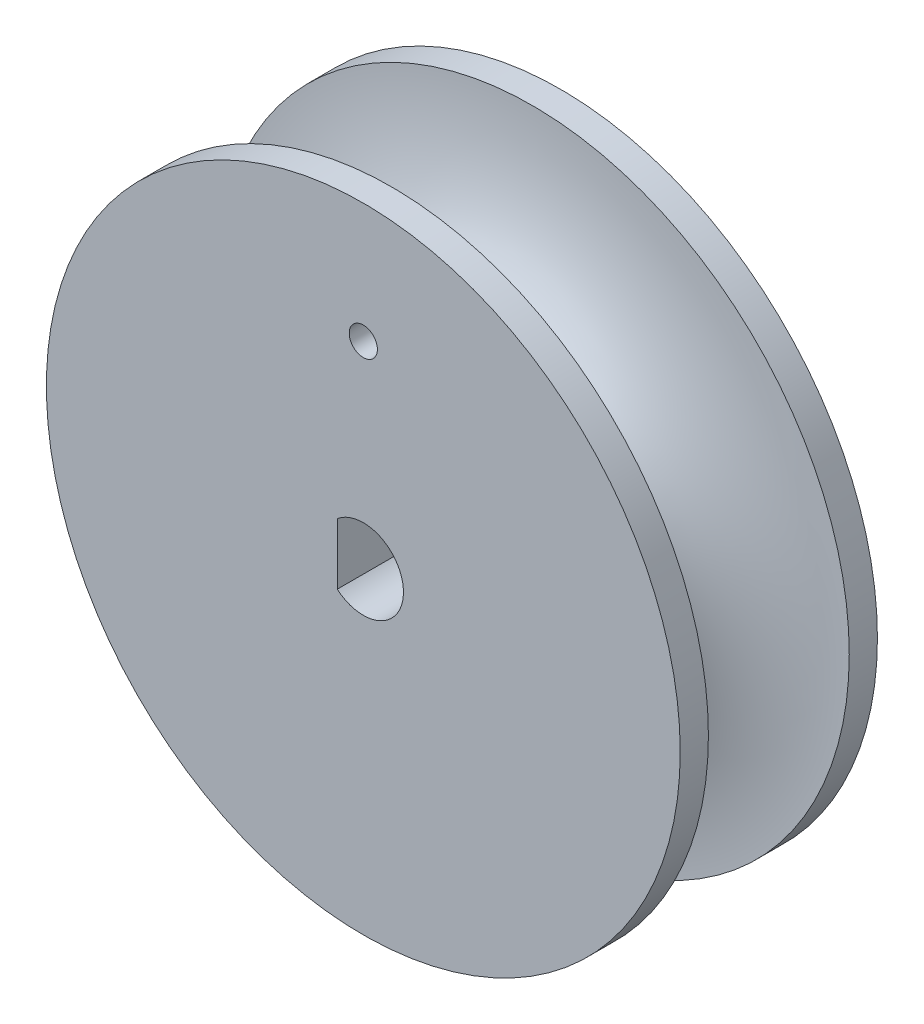
SolidWorks part; units mm, degrees
ref_plane "Front Plane" through (0, 0, 0) normal (0, 0, 1) x (1, 0, 0)
ref_plane "Top Plane" through (0, 0, 0) normal (0, 1, 0) x (1, 0, 0)
ref_plane "Right Plane" through (0, 0, 0) normal (1, 0, 0) x (0, 0, -1)
sketch "Sketch4" plane through (0, 0, 0) normal (1, 0, 0) x (0, 0, -1)
  line L0 (0, 0) -> (10.7579, 0) construction
  line L1 (-3.5, 11.25) -> (3.5, 11.25)
  line L2 (-3.5, 11.25) -> (-3.5, 1.425)
  line L3 (-3.5, 1.425) -> (3.5, 1.425)
  line L4 (3.5, 11.25) -> (3.5, 1.425)
  ellipse E0 centre (0, 11.25) end of major axis (0, 5.6898) minor radius 2.5
  dimension "D5" = 1
  dimension "D1" = 1.425
  dimension "D2" = 7
  dimension "D3" = 9.825
  dimension "D4" = 3.5
  dimension "D7" = 5.5602
revolve "Revolve1" add sketch "Sketch4" angle 360 about L0
sketch "Sketch7" plane through (0, 0, 3.5) normal (0, 0, 1) x (1, 0, 0)
  line L0 (-0.925, 1.084) -> (-0.925, -1.084)
  circle A0 centre (0, 0) radius 1.425 construction
  arc A1 (-0.925, -1.084) -> (-0.925, 1.084) centre (0, 0) cw
  point P5 (-0.925, 0)
  point P7 (-1.425, 0)
  dimension "D1" = 0.5
extrude "Boss-Extrude1" add sketch "Sketch7" against normal blind 7
sketch "Sketch8" plane through (0, 0, 3.5) normal (0, 0, 1) x (1, 0, 0)
  circle A0 centre (0, 7) radius 0.5
  dimension "D1" = 1
  dimension "D2" = 7
extrude "Cut-Extrude1" cut sketch "Sketch8" against normal blind 3
